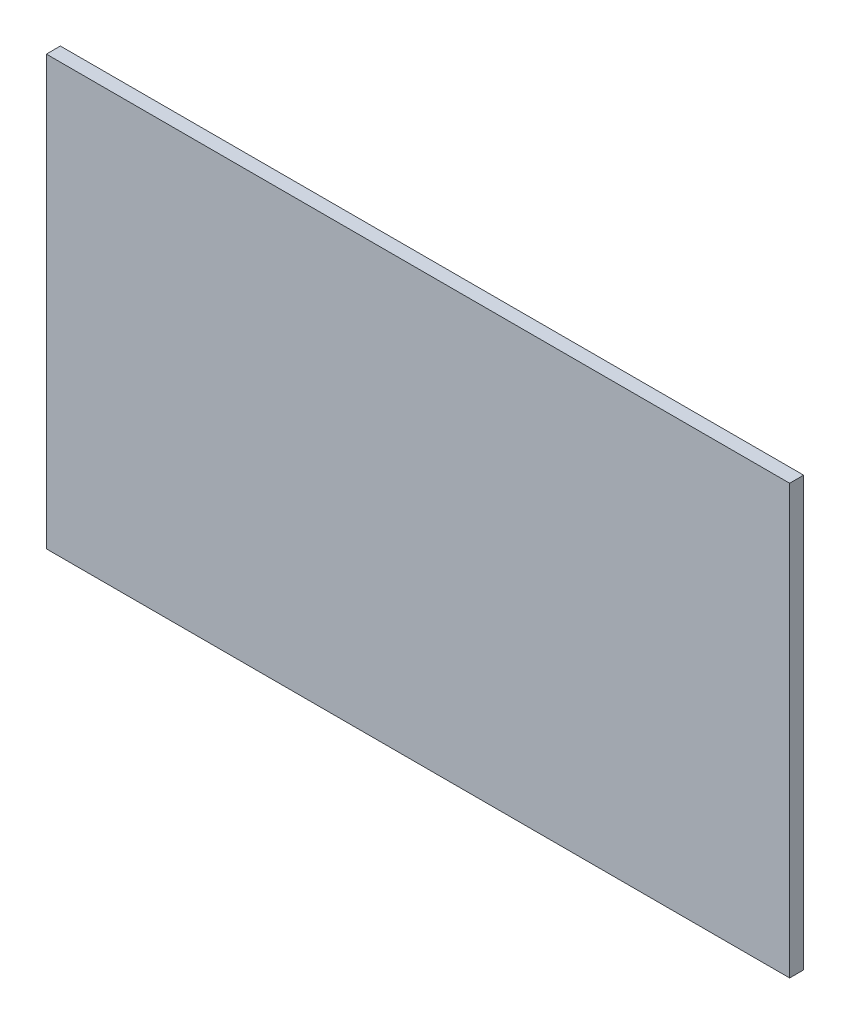
SolidWorks part; units mm, degrees
ref_plane "正面" through (0, 0, 0) normal (0, 0, 1) x (1, 0, 0)
ref_plane "平面" through (0, 0, 0) normal (0, 1, 0) x (1, 0, 0)
ref_plane "右側面" through (0, 0, 0) normal (1, 0, 0) x (0, 0, -1)
sketch "ｽｹｯﾁ1" plane through (0, 0, 0) normal (0, 0, 1) x (1, 0, 0)
  line L1 (-73.8944, 61.9929) -> (11.1056, 61.9929)
  line L2 (-73.8944, 61.9929) -> (-73.8944, 12.9929)
  line L3 (-73.8944, 12.9929) -> (11.1056, 12.9929)
  line L4 (11.1056, 61.9929) -> (11.1056, 12.9929)
  dimension "D3" = 49
  dimension "D4" = 85
extrude "ﾎﾞｽ - 押し出し1" add sketch "ｽｹｯﾁ1" along normal blind 1.6
